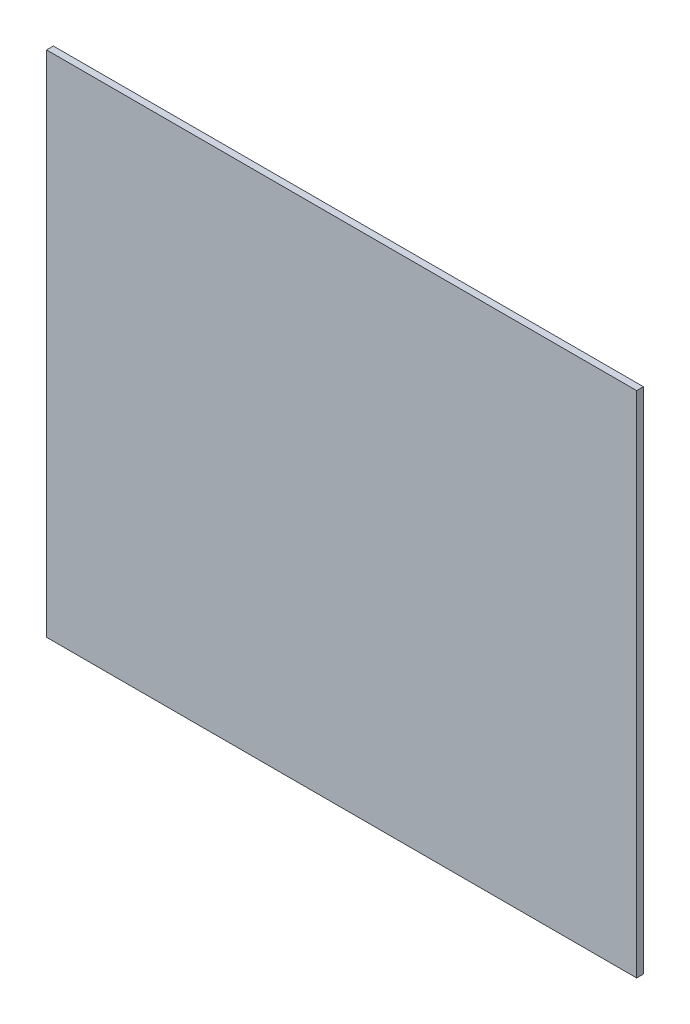
SolidWorks part; units mm, degrees
ref_plane "Plan de face" through (0, 0, 0) normal (0, 0, 1) x (1, 0, 0)
ref_plane "Plan de dessus" through (0, 0, 0) normal (0, 1, 0) x (1, 0, 0)
ref_plane "Plan de droite" through (0, 0, 0) normal (1, 0, 0) x (0, 0, -1)
sketch "Esquisse1" plane through (0, 0, 0) normal (0, 0, 1) x (1, 0, 0)
  line L1 (-33.1728, 31.2835) -> (53.8272, 31.2835)
  line L2 (-33.1728, 31.2835) -> (-33.1728, -43.7165)
  line L3 (-33.1728, -43.7165) -> (53.8272, -43.7165)
  line L4 (53.8272, 31.2835) -> (53.8272, -43.7165)
  dimension "D1" = 87
  dimension "D2" = 75
extrude "Boss.-Extru.1" add sketch "Esquisse1" along normal blind 1
sketch "Esquisse2" plane through (-33.1728, 0, 0) normal (-1, 0, 0) x (0, 0, 1)
  line L0 (1, 31.2835) -> (1, -43.7165) construction
  line L1 (1, 3.7835) -> (-9, 3.7835)
  line L2 (1, 3.7835) -> (1, -16.2165)
  line L3 (1, -16.2165) -> (-9, -16.2165)
  line L4 (-9, 3.7835) -> (-9, -16.2165)
  line L5 (0, 31.2835) -> (0, 3.7835) construction
  line L6 (0, 31.2835) -> (0, -43.7165) construction
  dimension "D1" = 10
  dimension "D2" = 20
extrude "Boss.-Extru.2" add sketch "Esquisse2" against normal blind 5
